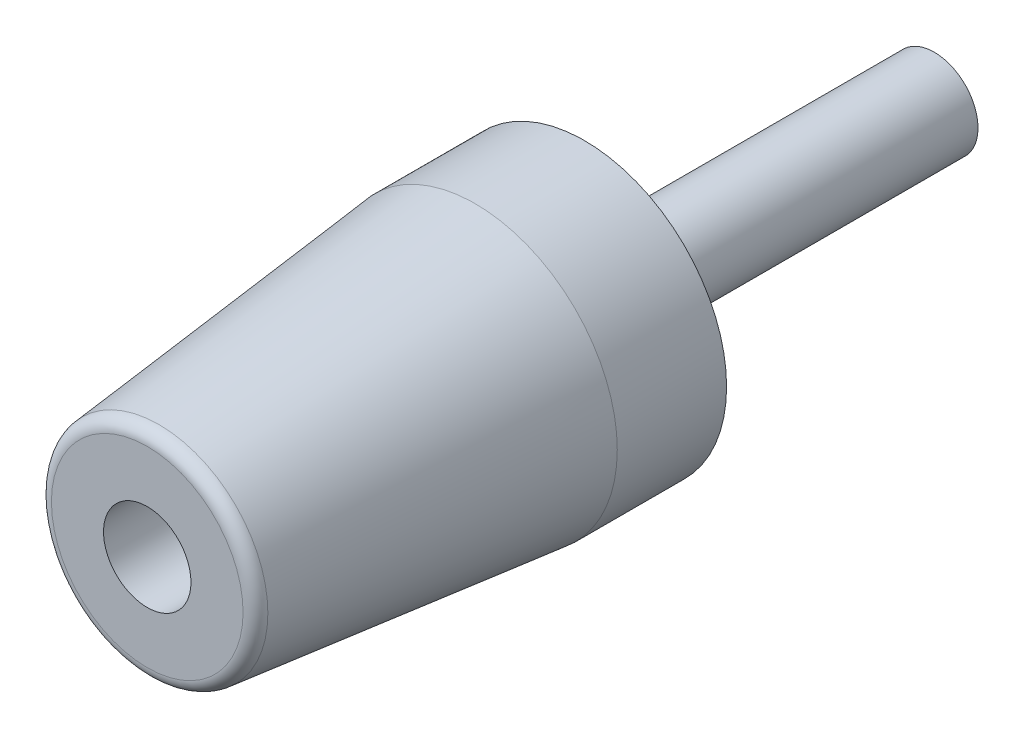
SolidWorks part; units mm, degrees
ref_plane "前视基准面" through (0, 0, 0) normal (0, 0, 1) x (1, 0, 0)
ref_plane "上视基准面" through (0, 0, 0) normal (0, 1, 0) x (1, 0, 0)
ref_plane "右视基准面" through (0, 0, 0) normal (1, 0, 0) x (0, 0, -1)
sketch "草图1" plane through (0, 0, 0) normal (0, 0, 1) x (1, 0, 0)
  circle A0 centre (0, 0) radius 2
  dimension "D1" = 4
extrude "凸台-拉伸1" add sketch "草图1" along normal blind 36
ref_plane "基准面1" through (0, 0, 16) normal (0, 0, 1) x (1, 0, 0)
sketch "草图2" plane through (0, 0, 16) normal (0, 0, 1) x (1, 0, 0)
  circle A0 centre (0, 0) radius 6.5
  dimension "D1" = 13
extrude "凸台-拉伸2" add sketch "草图2" along normal blind 5
sketch "草图3" plane through (0, 0, 21) normal (0, 0, 1) x (1, 0, 0)
  circle A0 centre (0, 0) radius 6.5
extrude "凸台-拉伸3" add sketch "草图3" along normal up to surface (15 mm away) draft 6
sketch "草图4" plane through (0, 0, 36) normal (0, 0, 1) x (1, 0, 0)
  circle A0 centre (0, 0) radius 2
  dimension "D1" = 4
extrude "切除-拉伸1" cut sketch "草图4" against normal blind 13
fillet "圆角1" radius 0.6 1 edges at (4.9234, 0, 36)
